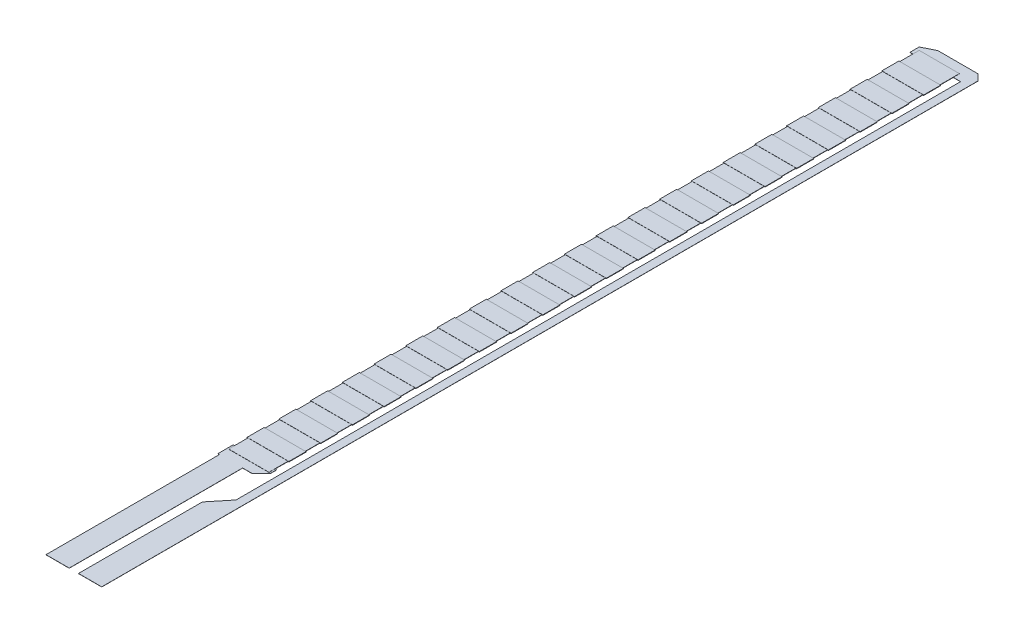
SolidWorks part; units mm, degrees
ref_plane "Front Plane" through (0, 0, 0) normal (0, 0, 1) x (1, 0, 0)
ref_plane "Top Plane" through (0, 0, 0) normal (0, 1, 0) x (1, 0, 0)
ref_plane "Right Plane" through (0, 0, 0) normal (1, 0, 0) x (0, 0, -1)
sketch "Sketch1" plane through (0, 13.0256, 0) normal (0, 1, 0) x (1, 0, 0)
  line L1 (-49.1053, -54.2802) -> (-47.2003, -54.2802)
  line L2 (-49.1053, -54.2802) -> (-49.1053, -44.1202)
  line L3 (-52.0263, 17.6018) -> (-51.0103, 18.1098)
  line L4 (-47.2003, -54.2802) -> (-47.2003, -44.1202)
  line L7 (-47.8646, -42.5962) -> (-47.8646, 16.8398)
  line L8 (-49.8673, -40.0562) -> (-49.1053, -40.0562)
  line L9 (-47.2003, -42.5962) -> (-47.2003, 16.8398)
  line L10 (-47.8646, 16.8398) -> (-52.0263, 16.8398)
  line L11 (-47.2003, 16.8398) -> (-47.2003, 17.6018)
  line L12 (-47.7083, 18.1098) -> (-51.0103, 18.1098)
  line L13 (-52.0263, 16.8398) -> (-52.0263, 17.6018)
  line L14 (-51.7723, -54.2802) -> (-49.8673, -54.2802)
  line L15 (-51.7723, -54.2802) -> (-51.7723, -40.0562)
  line L16 (-51.8993, -40.0562) -> (-51.7723, -40.0562)
  line L17 (-49.8673, -54.2802) -> (-49.8673, -40.0562)
  line L18 (-51.8993, -40.0562) -> (-51.8993, -38.7862)
  line L19 (-51.8993, -38.7862) -> (-48.3433, -38.7862)
  line L20 (-48.3433, -39.2942) -> (-48.3433, -38.7862)
  line L21 (-49.1053, -40.0562) -> (-48.3433, -39.2942)
  line L22 (-49.1053, -44.1202) -> (-47.8646, -42.5962)
  line L23 (-47.2003, -42.5962) -> (-47.2003, -44.1202)
  line L24 (-47.7083, 18.1098) -> (-47.2003, 17.6018)
  dimension "D2" = 1.905
  dimension "D3" = 10.16
  dimension "D4" = 59.436
  dimension "D5" = 1.016
  dimension "D7" = 4.826
  dimension "D8" = 0.508
  dimension "D9" = 0.508
  dimension "D10" = 0.508
  dimension "D11" = 1.905
  dimension "D14" = 1.27
  dimension "D15" = 3.556
  dimension "D16" = 0.762
  dimension "D18" = 0.762
extrude "Boss-Extrude1" add sketch "Sketch1" along normal blind 0.0127
sketch "Sketch2" plane through (0, 13.0256, 0) normal (0, 1, 0) x (1, 0, 0)
  line L1 (-51.7723, -39.2942) -> (-48.4703, -39.2942)
  line L2 (-51.7723, -39.2942) -> (-51.7723, 17.3478)
  line L3 (-51.7723, 17.3478) -> (-48.4703, 17.3478)
  line L4 (-48.4703, -39.2942) -> (-48.4703, 17.3478)
  dimension "D1" = 3.302
  dimension "D3" = 56.642
extrude "Boss-Extrude2" add sketch "Sketch2" along normal blind 0.0254
sketch "Sketch3" plane through (0, 13.0256, 0) normal (0, 1, 0) x (1, 0, 0)
  line L0 (-51.7723, 17.3478) -> (-51.7723, -39.2942) construction
  line L1 (-51.8358, -36.3224) -> (-48.4068, -36.3224)
  line L2 (-51.8358, -36.3224) -> (-51.8358, -37.7194)
  line L3 (-51.8358, -37.7194) -> (-48.4068, -37.7194)
  line L4 (-48.4068, -36.3224) -> (-48.4068, -37.7194)
  line L5 (-51.7723, -39.2942) -> (-48.4703, -39.2942) construction
  dimension "D1" = 3.429
  dimension "D2" = 1.397
  dimension "D3" = 0.0635
  dimension "D4" = 1.5748
extrude "Boss-Extrude3" add sketch "Sketch3" along normal blind 0.0381
pattern_linear "LPattern1" count 21 spacing 2.6035 along (0, 0, -1) of "Boss-Extrude3"
